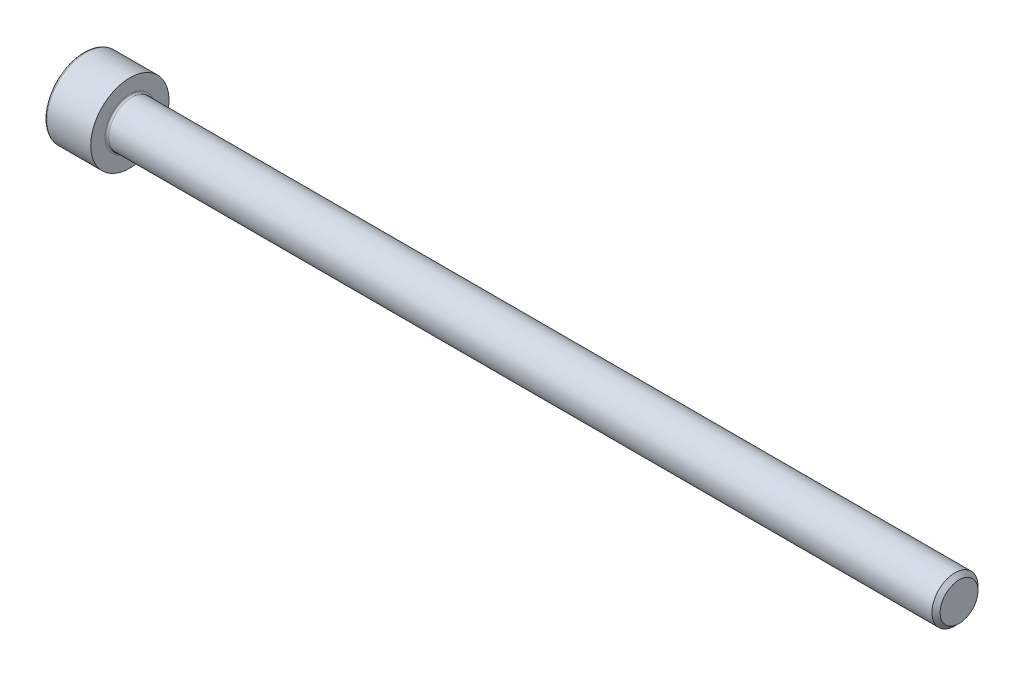
SolidWorks part; units mm, degrees
revolve "Base-Revolve" add sketch "BodySke"
sketch "BodySke" plane through (0, 0, 0) normal (0, 0, 1) x (1, 0, 0)
  line L0 (0, 0) -> (0, 4.25)
  line L1 (0, 4.25) -> (5, 4.25)
  line L2 (5, 4.25) -> (5, 2.5)
  line L3 (5, 2.5) -> (94.555, 2.5)
  line L4 (95, 2.055) -> (95, 0)
  line L5 (95, 0) -> (0, 0)
  line L6 (-31.75, 0) -> (127, 0) construction
  line L8 (95, 2.055) -> (94.555, 2.5)
  line L10 (95, -2.055) -> (94.555, -2.5) construction
  line L11 (5.8, 9.525) -> (5.8, 3.175) construction
  line L12 (5, 9.525) -> (5, 3.175) construction
  line L13 (35, 9.525) -> (35, 3.175) construction
  dimension "Body_ch_ang" = 45
  dimension "Thread_length" = 60
cosmetic thread "ThreadCosmetic" [suppressed]
fillet "Fillet1" radius 0.2 1 edges at (5, 0, 2.5)
fillet "Fillet2" radius 0.25 1 edges at (0, 0, 4.25)
ref_plane "Plane1" through (0, 0, 0) normal (0, 0, 1) x (1, 0, 0)
ref_plane "Plane2" through (0, 0, 0) normal (0, 1, 0) x (1, 0, 0)
ref_plane "Plane3" through (0, 0, 0) normal (1, 0, 0) x (0, 0, -1)
sketch "Sketch2" plane through (0, 0, 0) normal (0, 0, 1) x (1, 0, 0)
  line L0 (0, 2.042) -> (2.5, 2.042)
  line L1 (2.5, 2.042) -> (3.6789, 0)
  line L2 (-31.75, 0) -> (127, 0) construction
  line L3 (3.6789, 0) -> (0, 0)
  line L4 (0, 0) -> (0, 2.042)
  line L6 (0, 0) -> (47.625, 0) construction
  dimension "D2" = 60
  dimension "Depth" = 2.5
revolve "Hex-PreBroach" cut sketch "Sketch2" angle 360 about L6
sketch "Sketch3" plane through (0, 0, 0) normal (-1, 0, 0) x (0, 0.5, 0.866)
  line L0 (1.1789, 2.042) -> (-1.1789, 2.042)
  line L1 (-1.1789, 2.042) -> (-2.3579, 0)
  line L2 (1.1789, 2.042) -> (2.3579, 0)
  line L3 (1.1789, -2.042) -> (2.3579, 0)
  line L4 (1.1789, -2.042) -> (-1.1789, -2.042)
  line L5 (-1.1789, -2.042) -> (-2.3579, 0)
extrude "Hex" cut sketch "Sketch3" against normal blind 2.5
sketch "ThdSchSke" plane through (0, 0, 0) normal (0, 0, 1) x (1, 0, 0)
  line L0 (7.4, -2.055) -> (7.0884, -2.5)
  line L1 (7.4, -2.055) -> (7.7116, -2.5)
  line L2 (7.7116, -2.5) -> (7.7116, -3.125)
  line L3 (-3.175, 0) -> (5.1513, 0) construction
  line L4 (0, 4) -> (0, -4) construction
  line L5 (7.7116, -3.125) -> (7.0884, -3.125)
  line L6 (7.0884, -3.125) -> (7.0884, -2.5)
revolve "ThreadSchematic" [suppressed] cut sketch "ThdSchSke" angle 360 about L3
pattern_linear "ThdSchPat" [suppressed]
equation "\"D2@Sketch3\" = \"Hex_size@Sketch3\" / 2"
equation "\"D1@Sketch3\" = \"Hex_size@Sketch3\" / 2"
equation "\"D1@Sketch2\" = \"Hex_size@Sketch3\" / 2"
equation "\"Thread_minor@ThreadCosmetic\"  =  \"Minor_dia@BodySke\""
equation "\"Depth@Sketch2\" =  \"Key_eng@Hex\""
equation "\"Thread_length@ThreadCosmetic\" = ((sgn( (\"Length@BodySke\" - \"Advance@BodySke\" * 3.0) - \"Thread_nom@BodySke\" )-1)*( (\"Length@BodySke\" - \"Advance@BodySke\" * 3.0) - \"Thread_nom@BodySke\" ))/-2+ \"Thread_nom@BodySke\""
equation "\"Thread_minor@ThdSchSke\" = \"Minor_dia@BodySke\""
equation "\"Diameter@ThdSchSke\" = \"Diameter@BodySke\""
equation "\"Overcut@ThdSchSke\" = \"Diameter@BodySke\" * 1.25"
equation "\"Start@ThdSchSke\" = \"Head_ht@BodySke\" + \"Length@BodySke\" - \"Thread_length@ThreadCosmetic\"  '---Non-countersunk---"
equation "\"Num_threads@ThdSchPat\" = int( \"Thread_length@ThreadCosmetic\" / \"Advance@BodySke\" + 0.999 )  + 1"
equation "\"Advance@ThdSchPat\" = \"Thread_length@ThreadCosmetic\" /  (\"Num_threads@ThdSchPat\" - 1) 'relax it"
equation "\"Num_threads@ThdSchPat\" = \"Num_threads@ThdSchPat\" - sgn( \"Num_threads@ThdSchPat\" - 1) '---chamfered tips only---"
